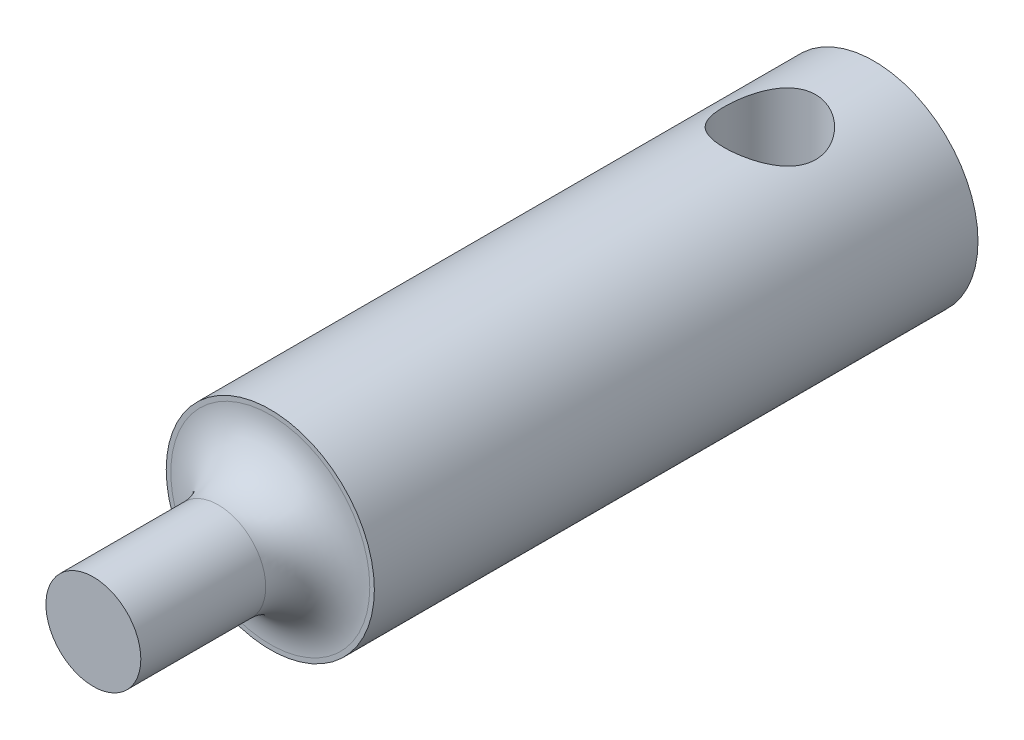
SolidWorks part; units mm, degrees
ref_plane "Front Plane" through (0, 0, 0) normal (0, 0, 1) x (1, 0, 0)
ref_plane "Top Plane" through (0, 0, 0) normal (0, 1, 0) x (1, 0, 0)
ref_plane "Right Plane" through (0, 0, 0) normal (1, 0, 0) x (0, 0, -1)
sketch "Sketch1" plane through (0, 0, 0) normal (0, 0, 1) x (1, 0, 0)
  circle A0 centre (0, 0) radius 3.175
  dimension "D1" = 6.35
extrude "Boss-Extrude1" add sketch "Sketch1" along normal blind 18.415
sketch "Sketch2" plane through (0, 0, 18.415) normal (0, 0, 1) x (1, 0, 0)
  circle A0 centre (0, 0) radius 1.4478
  dimension "D1" = 2.8956
extrude "Boss-Extrude2" add sketch "Sketch2" along normal blind 5.3975
fillet "Fillet1" radius 1.5875 1 edges at (1.4478, 0, 18.415)
sketch "Sketch3" plane through (0, 0, 0) normal (0, 1, 0) x (1, 0, 0)
  circle A0 centre (0, -3.175) radius 1.397
  point P2 (0, 0)
  dimension "D1" = 2.794
  dimension "D2" = 3.175
extrude "Cut-Extrude1" cut sketch "Sketch3" against normal through all and the other way through all
equation "\"D1@Boss-Extrude1\"=0.125+0.5 +0.1"
equation "\"D1@Boss-Extrude2\"=0.35 -0.2+ 0.0625"
